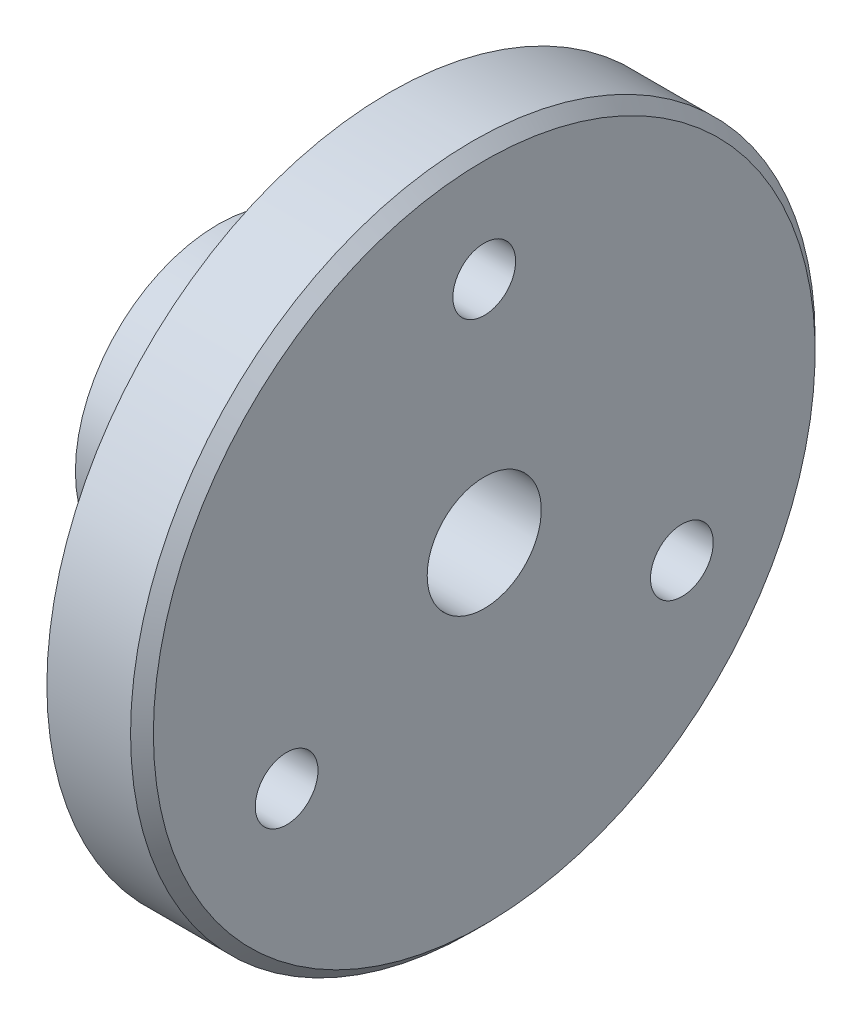
SolidWorks part; units mm, degrees
ref_plane "Plan de face" through (0, 0, 0) normal (0, 0, 1) x (1, 0, 0)
ref_plane "Plan de dessus" through (0, 0, 0) normal (0, 1, 0) x (1, 0, 0)
ref_plane "Plan de droite" through (0, 0, 0) normal (1, 0, 0) x (0, 0, -1)
sketch "Esquisse1" plane through (0, 0, 0) normal (0, 0, 1) x (1, 0, 0)
  line L0 (0, 0) -> (10.7365, 0) construction
  line L1 (0, 3) -> (14, 3)
  line L2 (14, 3) -> (14, 18)
  line L3 (14, 18) -> (9, 18)
  line L4 (9, 18) -> (9, 7.5)
  line L7 (0, 3) -> (0, 7.5)
  line L8 (0, 7.5) -> (9, 7.5)
  point P5 (0, 0)
  dimension "D1" = 6
  dimension "D3" = 36
  dimension "D4" = 5
  dimension "D5" = 15
  dimension "D6" = 9
revolve "Révolution1" add sketch "Esquisse1" angle 360 about L0
sketch "Esquisse2" plane through (0, 0, 0) normal (0, 0, 1) x (1, 0, 0)
  line L0 (14, -18) -> (14, 18) construction
  circle A0 centre (6, 0) radius 1.25
  dimension "D1" = 2.5
  dimension "D2" = 8
extrude "Enlèv. mat.-Extru.1" cut sketch "Esquisse2" against normal through all
hole_wizard "Trou taraudé M41" positions "Esquisse4" profile "Esquisse5" tap size "M4" standard "ISO" end condition through all
sketch "Esquisse4" plane through (14, 0, 0) normal (1, 0, 0) x (0, 0, -1)
  line L0 (0, 12) -> (0, 0) construction
  point P0 (0, 12)
  dimension "D1" = 12
sketch "Esquisse5" plane through (14, 12, 0) normal (0, 1, 0) x (0, 0, -1)
  line L0 (0, 0) -> (0, 14)
  line L1 (0, 14) -> (1.65, 14)
  line L2 (1.65, 14) -> (1.65, 0)
  line L5 (1.65, 0) -> (0, 0)
  line L11 (0, -6.35) -> (0, 107.95) construction
  dimension "Diamètre du trou pour taraudage jusqu'au prochain" = 3.3
  dimension "Profondeur du trou pour taraudage jusqu'au prochain" = 14
cosmetic thread "Filetage de perçage1" parameters "D2"=4
pattern_circular "Répétition circulaire1" count 3 over 360 about axis through (0, 0, 0) along (1, 0, 0) of "Trou taraudé M41"
cosmetic thread "Filetage de perçage2" parameters "D2"=4
cosmetic thread "Filetage de perçage3" parameters "D2"=4
chamfer "Chanfrein1" distance 0.6 angle 45 1 edges at (14, 0, 18)
